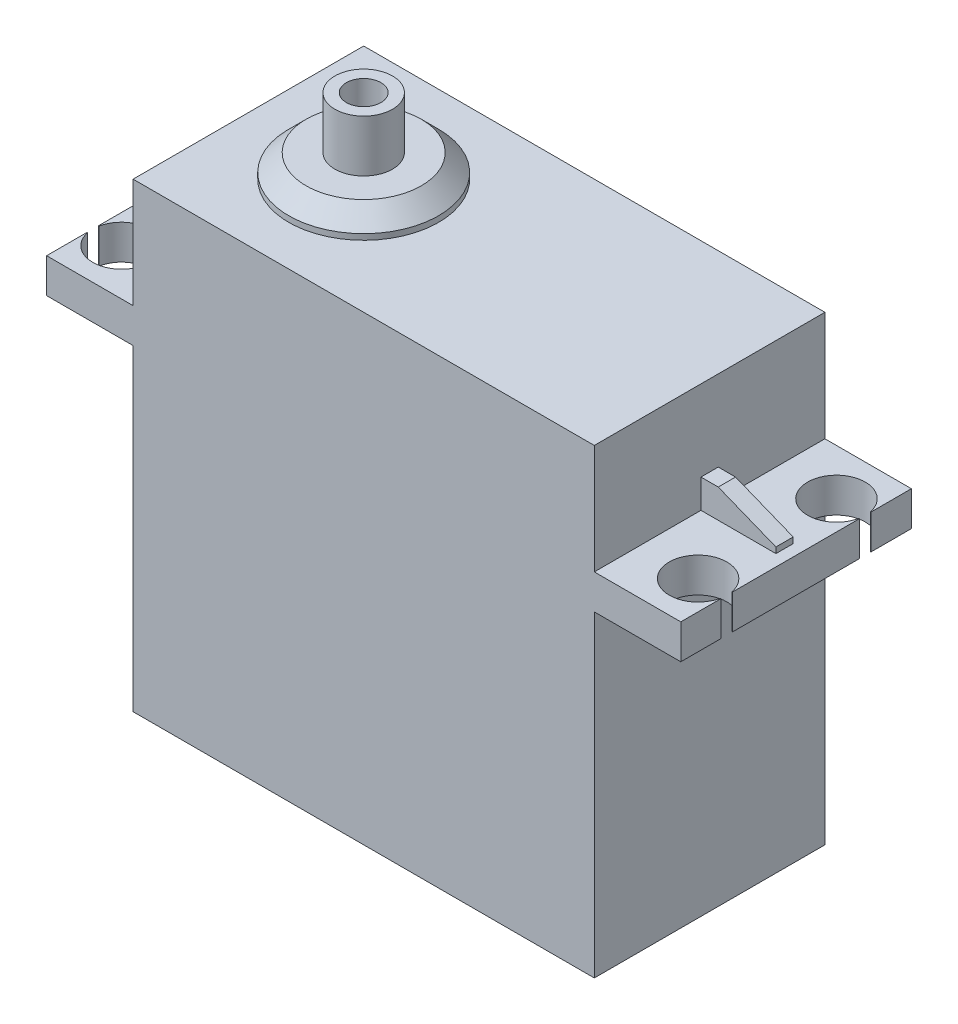
SolidWorks part; units mm, degrees
ref_plane "Front Plane" through (0, 0, 0) normal (0, 0, 1) x (1, 0, 0)
ref_plane "Top Plane" through (0, 0, 0) normal (0, 1, 0) x (1, 0, 0)
ref_plane "Right Plane" through (0, 0, 0) normal (1, 0, 0) x (0, 0, -1)
sketch "Sketch1" plane through (0, 0, 0) normal (0, 0, 1) x (1, 0, 0)
  line L1 (-20, 20) -> (20, 20)
  line L2 (-20, 20) -> (-20, -20)
  line L3 (-20, -20) -> (20, -20)
  line L4 (20, 20) -> (20, -20)
  line L5 (-20, 20) -> (20, -20) construction
  line L6 (-20, -20) -> (20, 20) construction
  point P0 (0, 0)
  dimension "D1" = 40
  dimension "D2" = 40
extrude "Boss-Extrude1" add sketch "Sketch1" along normal mid plane 20
sketch "Sketch2" plane through (0, 20, 0) normal (0, 1, 0) x (1, 0, 0)
  line L0 (20, -10) -> (20, 10) construction
  circle A0 centre (-10, 0) radius 6.5
  dimension "D1" = 30
  dimension "D2" = 13
extrude "Boss-Extrude2" add sketch "Sketch2" along normal blind 2
ref_plane "Plane1" through (0, 7.5, 0) normal (0, -1, 0) x (-1, 0, 0)
sketch "Sketch3" plane through (0, 7.5, 0) normal (0, -1, 0) x (-1, 0, 0)
  line L0 (20, -10) -> (20, 10) construction
  line L1 (20, -10) -> (27.5, -10)
  line L2 (20, -10) -> (20, 10)
  line L3 (20, 10) -> (27.5, 10)
  line L4 (27.5, -10) -> (27.5, 10)
  line L5 (-20, -10) -> (-20, 10) construction
  line L6 (-20, -10) -> (-27.5, -10)
  line L7 (-20, -10) -> (-20, 10)
  line L8 (-20, 10) -> (-27.5, 10)
  line L9 (-27.5, -10) -> (-27.5, 10)
  point P12 (20, 0)
  point P13 (20, 0)
  point P14 (27.5, 0)
  point P15 (-27.5, 0)
  dimension "D1" = 7.5
  dimension "D2" = 20
extrude "Boss-Extrude3" add sketch "Sketch3" against normal blind 3
sketch "Sketch4" plane through (0, 10.5, 0) normal (0, 1, 0) x (1, 0, 0)
  line L0 (20, -10) -> (20, 10) construction
  line L1 (20, 0.75) -> (26.5, 0.75)
  line L2 (20, 0.75) -> (20, -0.75)
  line L3 (20, -0.75) -> (26.5, -0.75)
  line L4 (26.5, 0.75) -> (26.5, -0.75)
  line L5 (27.5, 10) -> (27.5, -10) construction
  line L6 (20, -10) -> (20, 10) construction
  point P10 (20, 0)
  point P11 (20, 0)
  dimension "D1" = 1
  dimension "D2" = 1.5
extrude "Boss-Extrude4" add sketch "Sketch4" along normal blind 2.5
sketch "Sketch5" plane through (0, 0, 0.75) normal (0, 0, 1) x (1, 0, 0)
  line L0 (26.5, 11) -> (21.5, 13)
  line L1 (26.5, 13) -> (26.5, 10.5) construction
  line L2 (20, 13) -> (26.5, 13) construction
  line L3 (21.5, 13) -> (26.5, 13)
  line L4 (26.5, 13) -> (26.5, 11)
  dimension "D1" = 2
  dimension "D2" = 5
extrude "Cut-Extrude1" cut sketch "Sketch5" against normal blind 2.5
sketch "Sketch6" plane through (0, 10.5, 0) normal (0, 1, 0) x (1, 0, 0)
  line L0 (-27.5, 10) -> (-20, 10) construction
  line L1 (-20, 10) -> (-20, -10) construction
  line L3 (-20, -10) -> (-27.5, -10) construction
  line L4 (-20, 10) -> (-20, -10) construction
  line L5 (-27.4495, 6.5) -> (-27.5, 6.5)
  line L6 (-27.5, -10) -> (-27.5, 10) construction
  line L7 (-27.5, 6.5) -> (-27.5, 5.5)
  line L8 (-27.5, 5.5) -> (-27.4495, 5.5)
  line L9 (-27.4495, -5.5) -> (-27.5, -5.5)
  line L10 (-27.5, -5.5) -> (-27.5, -6.5)
  line L11 (-27.5, -6.5) -> (-27.4495, -6.5)
  arc A0 (-27.4495, 5.5) -> (-27.4495, 6.5) centre (-25, 6) ccw
  arc A1 (-27.4495, -6.5) -> (-27.4495, -5.5) centre (-25, -6) ccw
  point P1 (-27.5, 6)
  point P9 (-27.5, -6)
  dimension "D1" = 5
  dimension "D2" = 4
  dimension "D3" = 5
  dimension "D4" = 4
  dimension "D5" = 5
  dimension "D6" = 1
  dimension "D7" = 1
extrude "Cut-Extrude6" cut sketch "Sketch6" against normal blind 12.5
mirror "Mirror1" about plane through (0, 0, 0) normal (1, 0, 0) of "Cut-Extrude6", "Boss-Extrude4", "Cut-Extrude1"
chamfer "Chamfer1" distance 1.5 angle 45 1 edges at (-10, 22, 6.5)
sketch "Sketch7" plane through (0, 22, 0) normal (0, 1, 0) x (1, 0, 0)
  line L0 (-10.05, 2.75) -> (-9.95, 2.75)
  line L1 (-10.05, 2.75) -> (-10.303, 2.5925)
  line L2 (-9.95, 2.75) -> (-9.697, 2.5925)
  line L3 (-9.4145, 2.6874) -> (-9.697, 2.5925)
  line L4 (-9.4145, 2.6874) -> (-9.3172, 2.6643)
  line L5 (-9.3172, 2.6643) -> (-9.1073, 2.4527)
  line L6 (-8.8105, 2.4799) -> (-9.1073, 2.4527)
  line L7 (-8.8105, 2.4799) -> (-8.7211, 2.435)
  line L8 (-8.7211, 2.435) -> (-8.5657, 2.1807)
  line L9 (-8.2706, 2.1388) -> (-8.5657, 2.1807)
  line L10 (-8.2706, 2.1388) -> (-8.194, 2.0745)
  line L11 (-8.194, 2.0745) -> (-8.1014, 1.7912)
  line L12 (-7.824, 1.6823) -> (-8.1014, 1.7912)
  line L13 (-7.824, 1.6823) -> (-7.7643, 1.6021)
  line L14 (-7.7643, 1.6021) -> (-7.7395, 1.3051)
  line L15 (-7.4947, 1.1351) -> (-7.7395, 1.3051)
  line L16 (-7.4947, 1.1351) -> (-7.4551, 1.0433)
  line L17 (-7.4551, 1.0433) -> (-7.4995, 0.7486)
  line L18 (-7.3005, 0.5268) -> (-7.4995, 0.7486)
  line L19 (-7.3005, 0.5268) -> (-7.2831, 0.4283)
  line L20 (-7.2831, 0.4283) -> (-7.3943, 0.1518)
  line L21 (-7.2517, -0.11) -> (-7.3943, 0.1518)
  line L22 (-7.2517, -0.11) -> (-7.2576, -0.2098)
  line L23 (-7.2576, -0.2098) -> (-7.4295, -0.4532)
  line L24 (-7.3512, -0.7408) -> (-7.4295, -0.4532)
  line L25 (-7.3512, -0.7408) -> (-7.3799, -0.8366)
  line L26 (-7.3799, -0.8366) -> (-7.6033, -1.0338)
  line L27 (-7.5934, -1.3317) -> (-7.6033, -1.0338)
  line L28 (-7.5934, -1.3317) -> (-7.6434, -1.4183)
  line L29 (-7.6434, -1.4183) -> (-7.9063, -1.5587)
  line L30 (-7.9654, -1.8508) -> (-7.9063, -1.5587)
  line L31 (-7.9654, -1.8508) -> (-8.034, -1.9235)
  line L32 (-8.034, -1.9235) -> (-8.3222, -1.9995)
  line L33 (-8.4471, -2.2701) -> (-8.3222, -1.9995)
  line L34 (-8.4471, -2.2701) -> (-8.5306, -2.3251)
  line L35 (-8.5306, -2.3251) -> (-8.8286, -2.3325)
  line L36 (-9.0125, -2.5671) -> (-8.8286, -2.3325)
  line L37 (-9.0125, -2.5671) -> (-9.1064, -2.6013)
  line L38 (-9.1064, -2.6013) -> (-9.3981, -2.5398)
  line L39 (-9.6311, -2.7256) -> (-9.3981, -2.5398)
  line L40 (-9.6311, -2.7256) -> (-9.7304, -2.7372)
  line L41 (-9.7304, -2.7372) -> (-10, -2.6101)
  line L42 (-10.2696, -2.7372) -> (-10, -2.6101)
  line L43 (-10.2696, -2.7372) -> (-10.3689, -2.7256)
  line L44 (-10.3689, -2.7256) -> (-10.6019, -2.5398)
  line L45 (-10.8936, -2.6013) -> (-10.6019, -2.5398)
  line L46 (-10.8936, -2.6013) -> (-10.9875, -2.5671)
  line L47 (-10.9875, -2.5671) -> (-11.1714, -2.3325)
  line L48 (-11.4694, -2.3251) -> (-11.1714, -2.3325)
  line L49 (-11.4694, -2.3251) -> (-11.5529, -2.2701)
  line L50 (-11.5529, -2.2701) -> (-11.6778, -1.9995)
  line L51 (-11.966, -1.9235) -> (-11.6778, -1.9995)
  line L52 (-11.966, -1.9235) -> (-12.0346, -1.8508)
  line L53 (-12.0346, -1.8508) -> (-12.0937, -1.5587)
  line L54 (-12.3566, -1.4183) -> (-12.0937, -1.5587)
  line L55 (-12.3566, -1.4183) -> (-12.4066, -1.3317)
  line L56 (-12.4066, -1.3317) -> (-12.3967, -1.0338)
  line L57 (-12.6201, -0.8366) -> (-12.3967, -1.0338)
  line L58 (-12.6201, -0.8366) -> (-12.6488, -0.7408)
  line L59 (-12.6488, -0.7408) -> (-12.5705, -0.4532)
  line L60 (-12.7424, -0.2098) -> (-12.5705, -0.4532)
  line L61 (-12.7424, -0.2098) -> (-12.7483, -0.11)
  line L62 (-12.7483, -0.11) -> (-12.6057, 0.1518)
  line L63 (-12.7169, 0.4283) -> (-12.6057, 0.1518)
  line L64 (-12.7169, 0.4283) -> (-12.6995, 0.5268)
  line L65 (-12.6995, 0.5268) -> (-12.5005, 0.7486)
  line L66 (-12.5449, 1.0433) -> (-12.5005, 0.7486)
  line L67 (-12.5449, 1.0433) -> (-12.5053, 1.1351)
  line L68 (-12.5053, 1.1351) -> (-12.2605, 1.3051)
  line L69 (-12.2357, 1.6021) -> (-12.2605, 1.3051)
  line L70 (-12.2357, 1.6021) -> (-12.176, 1.6823)
  line L71 (-12.176, 1.6823) -> (-11.8986, 1.7912)
  line L72 (-11.806, 2.0745) -> (-11.8986, 1.7912)
  line L73 (-11.806, 2.0745) -> (-11.7294, 2.1388)
  line L74 (-11.7294, 2.1388) -> (-11.4343, 2.1807)
  line L75 (-11.2789, 2.435) -> (-11.4343, 2.1807)
  line L76 (-11.2789, 2.435) -> (-11.1895, 2.4799)
  line L77 (-11.1895, 2.4799) -> (-10.8927, 2.4527)
  line L78 (-10.6828, 2.6643) -> (-10.8927, 2.4527)
  line L79 (-10.6828, 2.6643) -> (-10.5855, 2.6874)
  line L80 (-10.5855, 2.6874) -> (-10.303, 2.5925)
  line L81 (-10.303, 2.5925) -> (-10.55, 2.4387) construction
  line L82 (-9.697, 2.5925) -> (-9.45, 2.4387) construction
  circle A0 centre (-10, 0) radius 2.5
  circle A1 centre (-10, 0) radius 1.5
  point P10 (-10, 2.75)
  point P116 (-10, 0)
  dimension "D1" = 3
  dimension "D2" = 5
  dimension "D3" = 2.75
  dimension "D4" = 1.1
  dimension "D5" = 0.1
  dimension "D6" = 0.55
  dimension "D7" = 27
sketch "Sketch8" plane through (-20, 0, 0) normal (-1, 0, 0) x (0, 0, 1)
  line L0 (10, -20) -> (-10, -20) construction
  line L1 (-3.5, -9) -> (3.5, -9)
  line L2 (-3.5, -9) -> (-3.5, -13)
  line L3 (-3.5, -13) -> (3.5, -13)
  line L4 (3.5, -9) -> (3.5, -13)
  line L6 (-2.5, -10) -> (2.5, -10)
  line L7 (2.5, -10) -> (2.5, -12)
  line L8 (-2.5, -12) -> (2.5, -12)
  line L9 (-2.5, -10) -> (-2.5, -12)
  point P6 (0, -9)
  dimension "D1" = 7
  dimension "D2" = 7
  dimension "D3" = 4
  dimension "D4" = 1
extrude "Boss-Extrude6" add sketch "Sketch8" along normal blind 6
extrude "Boss-Extrude7" add sketch "Sketch7" along normal blind 4.5 contours A0 A1
